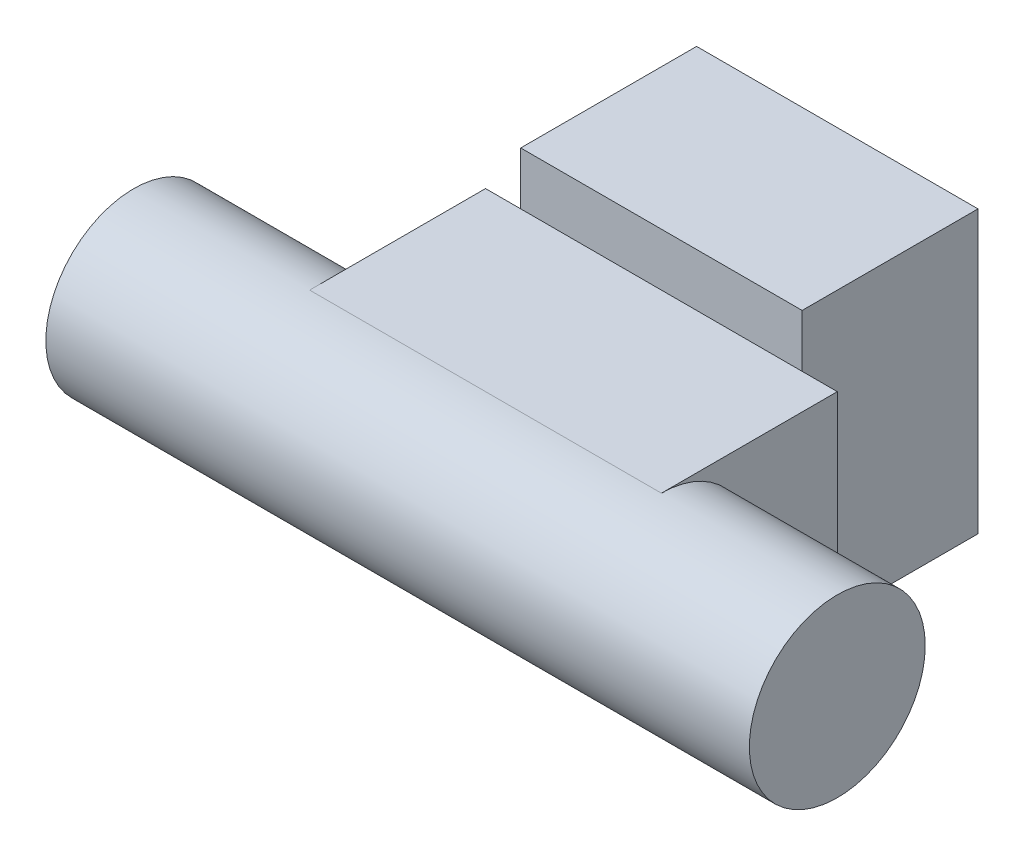
SolidWorks part; units mm, degrees
ref_plane "Front Plane" through (0, 0, 0) normal (0, 0, 1) x (1, 0, 0)
ref_plane "Top Plane" through (0, 0, 0) normal (0, 1, 0) x (1, 0, 0)
ref_plane "Right Plane" through (0, 0, 0) normal (1, 0, 0) x (0, 0, -1)
sketch "Sketch2" plane through (0, 0, 0) normal (0, 0, 1) x (1, 0, 0)
  line L1 (0, 0) -> (10, 0)
  line L2 (0, 0) -> (0, -10)
  line L3 (0, -10) -> (10, -10)
  line L4 (10, 0) -> (10, -10)
  dimension "D1" = 10
  dimension "D2" = 10
extrude "Boss-Extrude1" add sketch "Sketch2" along normal blind 10
sketch "Sketch3" plane through (0, 0, 0) normal (1, 0, 0) x (0, 0, -1)
  line L0 (-10, -10) -> (-10, 0) construction
  circle A0 centre (-10, -5) radius 5
extrude "Boss-Extrude2" add sketch "Sketch3" along normal blind 20
mirror "Mirror1" about plane through (0, 0, 10) normal (1, 0, 0) of "Boss-Extrude2", "Boss-Extrude1"
sketch "Sketch4" plane through (0, 0, 0) normal (0, 0, -1) x (-1, 0, 0)
  line L0 (10, -10) -> (10, 0) construction
  line L1 (-8, 3) -> (8, 3)
  line L2 (-8, 3) -> (-8, -13)
  line L3 (-8, -13) -> (8, -13)
  line L4 (8, 3) -> (8, -13)
  line L5 (10, -10) -> (-10, -10) construction
  point P4 (10, -5)
  point P7 (0, -10)
  dimension "D1" = 16
  dimension "D2" = 16
  dimension "D3" = 8
  dimension "D4" = 8
extrude "Boss-Extrude3" add sketch "Sketch4" along normal blind 10
sketch "Sketch5" plane through (0, 0, -10) normal (0, 0, -1) x (-1, 0, 0)
  circle A0 centre (0, -5) radius 5
  dimension "D1" = 10
extrude "Cut-Extrude1" cut sketch "Sketch5" against normal blind 4
sketch "Sketch6" plane through (0, 0, -6) normal (0, 0, -1) x (-1, 0, 0)
  circle A0 centre (0, -5) radius 7
  dimension "D1" = 14
extrude "Cut-Extrude2" cut sketch "Sketch6" against normal blind 4
